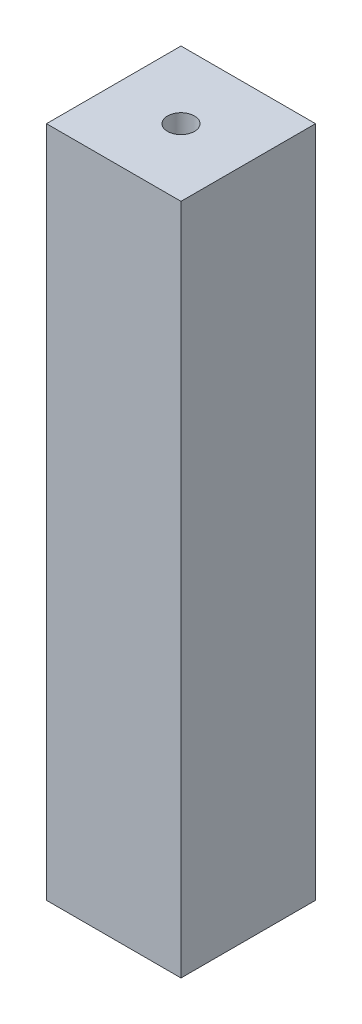
SolidWorks part; units mm, degrees
ref_plane "Front Plane" through (0, 0, 0) normal (0, 0, 1) x (1, 0, 0)
ref_plane "Top Plane" through (0, 0, 0) normal (0, 1, 0) x (1, 0, 0)
ref_plane "Right Plane" through (0, 0, 0) normal (1, 0, 0) x (0, 0, -1)
sketch "Sketch1" plane through (0, 0, 0) normal (0, 1, 0) x (1, 0, 0)
  line L1 (0, 0) -> (20, 0)
  line L2 (0, 0) -> (0, 20)
  line L3 (0, 20) -> (20, 20)
  line L4 (20, 0) -> (20, 20)
extrude "Boss-Extrude1" add sketch "Sketch1" along normal blind 100
sketch "Sketch2" plane through (0, 100, 0) normal (0, 1, 0) x (1, 0, 0)
  circle A0 centre (10, 10) radius 2
extrude "Cut-Extrude1" cut sketch "Sketch2" against normal blind 100
